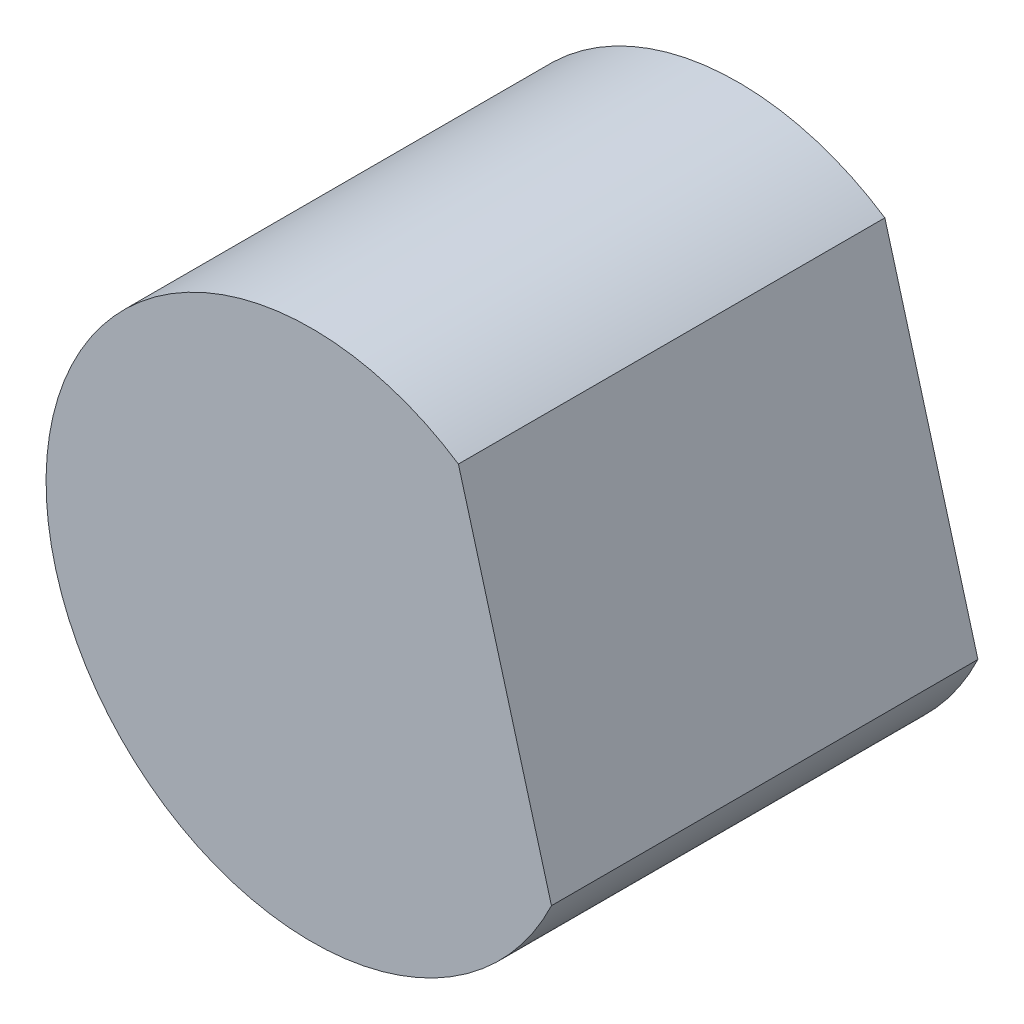
SolidWorks part; units mm, degrees
ref_plane "Front Plane" through (0, 0, 0) normal (0, 0, 1) x (1, 0, 0)
ref_plane "Top Plane" through (0, 0, 0) normal (0, 1, 0) x (1, 0, 0)
ref_plane "Right Plane" through (0, 0, 0) normal (1, 0, 0) x (0, 0, -1)
sketch "Sketch2" plane through (0, 0, 0) normal (0, 0, 1) x (1, 0, 0)
  circle A0 centre (0, 0) radius 38
  dimension "D1" = 76
extrude "Boss-Extrude1" add sketch "Sketch2" along normal blind 61 contours A0
sketch "Sketch3" plane through (0, 0, 0) normal (0, 0, -1) x (-1, 0, 0)
  line L0 (-34.4937, -17.1007) -> (-20.7814, 32.4096) construction
  line L1 (-34.292, -16.3725) -> (-20.9831, 31.6814)
  circle A0 centre (0, 0) radius 38 construction
  arc A3 (-20.9831, 31.6814) -> (-34.292, -16.3725) centre (0, 0) ccw
extrude "Cut-Extrude1" cut sketch "Sketch3" against normal up to surface (61 mm away) up to face at (38, 0, 61)
